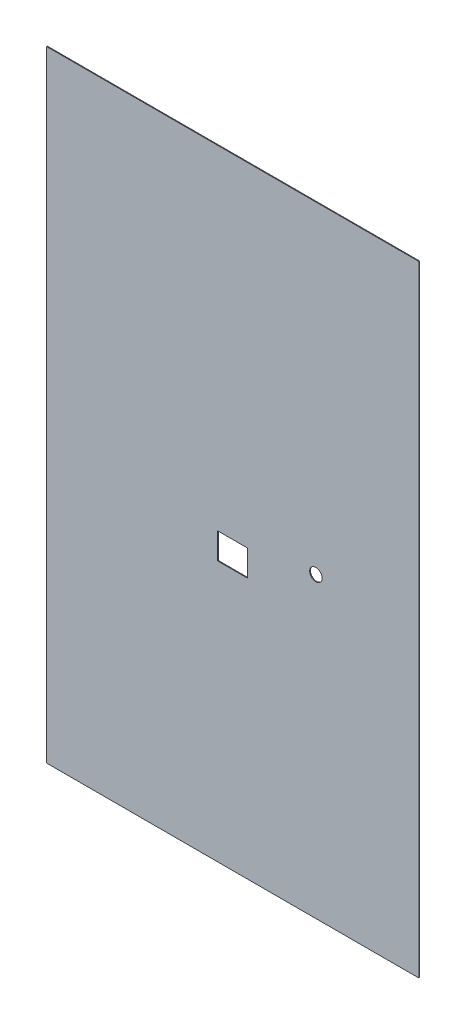
SolidWorks part; units mm, degrees
ref_plane "前基準面" through (0, 0, 0) normal (0, 0, 1) x (1, 0, 0)
ref_plane "上基準面" through (0, 0, 0) normal (0, 1, 0) x (1, 0, 0)
ref_plane "右基準面" through (0, 0, 0) normal (1, 0, 0) x (0, 0, -1)
sketch "草圖1" plane through (0, 0, 0) normal (0, 0, 1) x (1, 0, 0)
  line L1 (0, 0) -> (1500, 0)
  line L2 (0, 0) -> (0, -2500)
  line L3 (0, -2500) -> (1500, -2500)
  line L4 (1500, 0) -> (1500, -2500)
  dimension "D1" = 1500
  dimension "D2" = 2500
extrude "填料-伸長1" add sketch "草圖1" along normal blind 3
sketch "草圖2" plane through (0, 0, 3) normal (0, 0, 1) x (1, 0, 0)
  line L0 (750, 0) -> (750, -2500) construction
  line L1 (1500, 0) -> (0, 0) construction
  line L2 (0, -2500) -> (1500, -2500) construction
  circle A0 centre (750, -1300) radius 20
  dimension "D1" = 1200
  dimension "D2" = 40
extrude "除料-伸長1" [suppressed] cut sketch "草圖2" against normal through all
sketch "草圖3" plane through (0, 0, 3) normal (0, 0, 1) x (1, 0, 0)
  line L0 (750, 0) -> (750, -2500) construction
  line L1 (690, -1345) -> (810, -1345)
  line L2 (690, -1345) -> (690, -1450)
  line L3 (690, -1450) -> (810, -1450)
  line L4 (810, -1345) -> (810, -1450)
  line L5 (1500, 0) -> (0, 0) construction
  line L6 (0, -2500) -> (1500, -2500) construction
  dimension "D1" = 60
  dimension "D2" = 60
  dimension "D3" = 105
  dimension "D4" = 1050
extrude "除料-伸長2" cut sketch "草圖3" against normal through all
sketch "草圖4" plane through (0, 0, 3) normal (0, 0, 1) x (1, 0, 0)
  line L0 (0, -2500) -> (1500, -2500) construction
  circle A0 centre (1085.3679, -1300) radius 25
  dimension "D1" = 1200
  dimension "D2" = 50
extrude "除料-伸長3" cut sketch "草圖4" against normal blind 300
